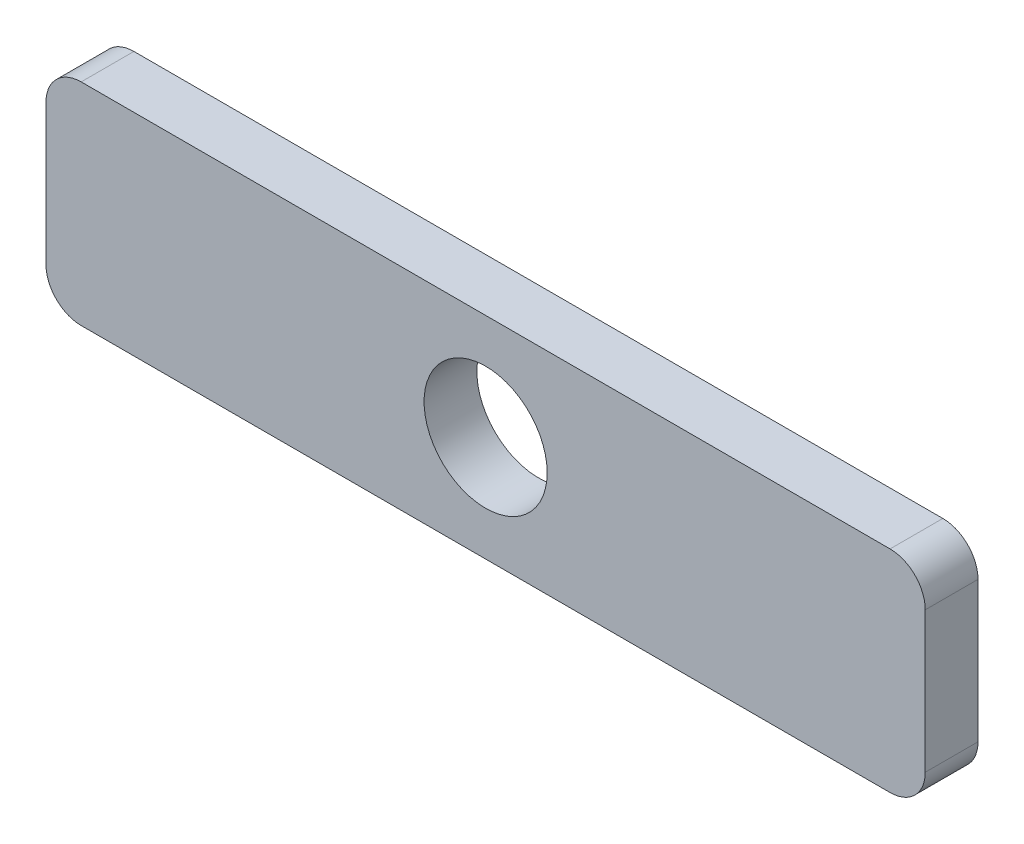
SolidWorks part; units mm, degrees
material "Plain Carbon Steel"
ref_plane "Front Plane" through (0, 0, 0) normal (0, 0, 1) x (1, 0, 0)
ref_plane "Top Plane" through (0, 0, 0) normal (0, 1, 0) x (1, 0, 0)
ref_plane "Right Plane" through (0, 0, 0) normal (1, 0, 0) x (0, 0, -1)
sketch "Sketch1" plane through (0, 0, 0) normal (0, 0, 1) x (1, 0, 0)
  line L1 (-25, -6) -> (25, -6)
  line L2 (-25, -6) -> (-25, 6)
  line L3 (-25, 6) -> (25, 6)
  line L4 (25, -6) -> (25, 6)
  line L5 (-25, -6) -> (25, 6) construction
  line L6 (-25, 6) -> (25, -6) construction
  circle A0 centre (0, 0) radius 3.5
  point P0 (0, 0)
  dimension "D2" = 7
  dimension "D1" = 50
  dimension "D3" = 12
extrude "Boss-Extrude1" add sketch "Sketch1" along normal blind 3
fillet "Fillet1" radius 2 4 edges at (25, -6, 1.5) (25, 6, 1.5) (-25, -6, 1.5) (-25, 6, 1.5)
